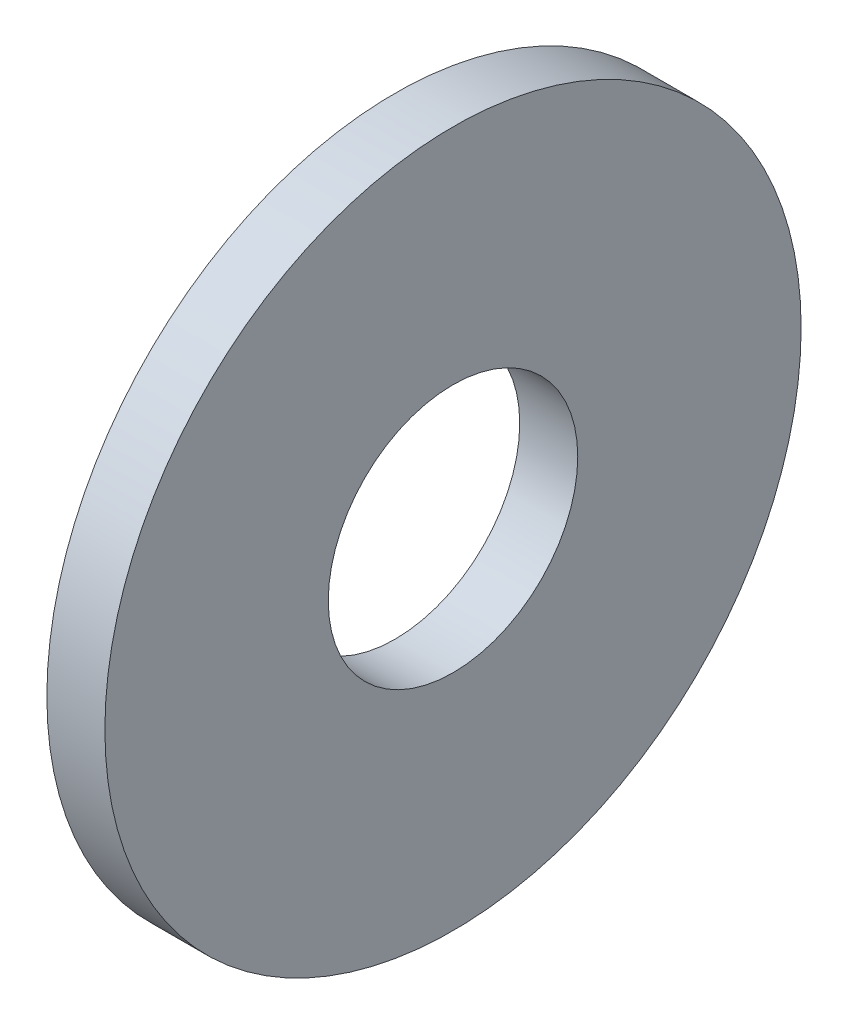
SolidWorks part; units mm, degrees
ref_plane "Plane1" through (0, 0, 0) normal (0, 0, 1) x (1, 0, 0)
ref_plane "Plane2" through (0, 0, 0) normal (0, 1, 0) x (1, 0, 0)
ref_plane "Plane3" through (0, 0, 0) normal (1, 0, 0) x (0, 0, -1)
revolve "Base-Revolve" add sketch "Sketch1" angle 360 about L0
sketch "Sketch1" plane through (0, 0, 0) normal (0, 0, 1) x (1, 0, 0)
  line L0 (-34.925, 0) -> (9.525, 0) construction
  line L1 (0, 2.15) -> (0, 6)
  line L2 (0, 6) -> (-1, 6)
  line L3 (-1, 6) -> (-1, 2.15)
  line L4 (-1, 2.15) -> (0, 2.15)
  dimension "Thickness" = 1
  dimension "Inside_dia" = 4.3
  dimension "Outside_dia" = 12
